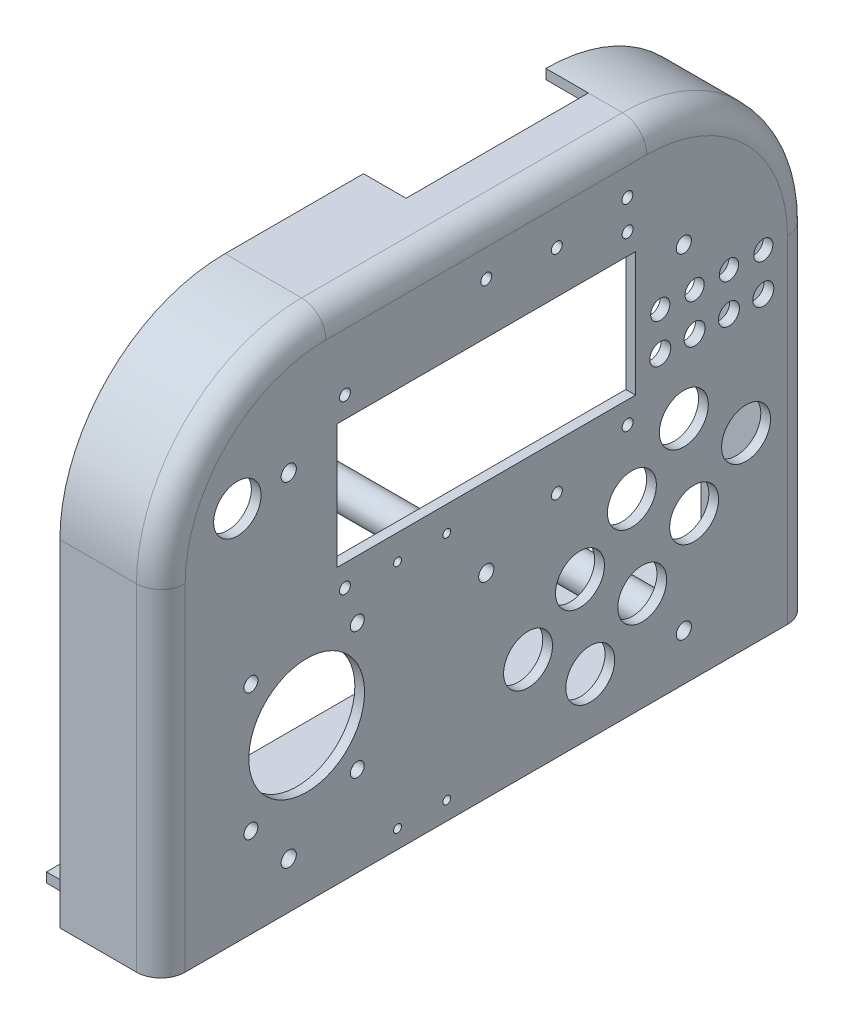
SolidWorks part; units mm, degrees
ref_plane "Front Plane" through (0, 0, 0) normal (0, 0, 1) x (1, 0, 0)
ref_plane "Top Plane" through (0, 0, 0) normal (0, 1, 0) x (1, 0, 0)
ref_plane "Right Plane" through (0, 0, 0) normal (1, 0, 0) x (0, 0, -1)
sketch "Sketch1" plane through (0, 0, 0) normal (1, 0, 0) x (0, 0, -1)
  line L0 (-107.09, -0.1) -> (107.09, -0.1) construction
  line L1 (-49.1, -20.45) -> (49.1, -20.45)
  line L2 (-49.1, -20.45) -> (-49.1, 20.45)
  line L3 (-49.1, 20.45) -> (49.1, 20.45)
  line L4 (49.1, -20.45) -> (49.1, 20.45)
  line L5 (-49.1, -20.45) -> (49.1, 20.45) construction
  line L6 (-49.1, 20.45) -> (49.1, -20.45) construction
  line L11 (-49.1, 29.95) -> (49.1, 29.95) construction
  line L12 (-49.1, 29.95) -> (-49.1, -30.15) construction
  line L13 (-49.1, -30.15) -> (49.1, -30.15) construction
  line L14 (49.1, 29.95) -> (49.1, -30.15) construction
  line L15 (-49.1, 20.45) -> (-82.6403, 20.45) construction
  line L16 (0, 0) -> (0, -0.1) construction
  line L17 (-46.5, -27.6) -> (46.5, -27.6) construction
  line L18 (-46.5, -27.6) -> (-46.5, 27.4) construction
  line L19 (-46.5, 27.4) -> (46.5, 27.4) construction
  line L20 (46.5, -27.6) -> (46.5, 27.4) construction
  line L21 (-46.5, -27.6) -> (46.5, 27.4) construction
  line L22 (-46.5, 27.4) -> (46.5, -27.6) construction
  line L23 (47.911, -49.4394) -> (85.4788, -49.4394) construction
  line L24 (65, -35.1) -> (85.4788, -49.4394) construction
  line L25 (47.911, -49.4394) -> (65, -35.1) construction
  line L26 (0, -0.1) -> (-71.6, -0.1) construction
  line L31 (0, -110.8) -> (0, 54.2) construction
  line L32 (-52.79, 54.2) -> (52.79, 54.2)
  line L33 (-59.95, -60.45) -> (-59.1, -60.45) construction
  line L34 (-42.45, -81.35) -> (-77.45, -81.35) construction
  line L35 (-42.45, -81.35) -> (-42.45, -39.55) construction
  line L36 (-42.45, -39.55) -> (-77.45, -39.55) construction
  line L37 (-77.45, -81.35) -> (-77.45, -39.55) construction
  line L38 (-42.45, -81.35) -> (-77.45, -39.55) construction
  line L39 (-42.45, -39.55) -> (-77.45, -81.35) construction
  line L40 (-107.09, -0.1) -> (-107.09, -110.8)
  line L41 (-107.09, -110.8) -> (107.09, -110.8)
  line L42 (107.09, -0.1) -> (107.09, -110.8)
  line L43 (0, -40.5) -> (0, -46.55) construction
  line L45 (-65, -95.5) -> (65, -95.5) construction
  line L46 (-65, -95.5) -> (-65, 14.5) construction
  line L47 (-65, 14.5) -> (65, 14.5) construction
  line L48 (65, -95.5) -> (65, 14.5) construction
  line L49 (-65, -95.5) -> (65, 14.5) construction
  line L50 (-65, 14.5) -> (65, -95.5) construction
  line L51 (46.42, 54.2) -> (46.42, 37.2) construction
  line L52 (0, 37.2) -> (46.42, 37.2) construction
  line L53 (23.21, 37.2) -> (23.21, -27.6) construction
  line L54 (-42.45, -81.35) -> (0, -81.35) construction
  line L56 (-29.2, -28.8) -> (-13, -28.8) construction
  line L58 (-29.2, -104.8) -> (-13, -104.8) construction
  line L59 (-29.2, -104.8) -> (-29.2, -28.8) construction
  line L60 (-29.2, -28.8) -> (-13, -28.8) construction
  line L61 (-13, -104.8) -> (-13, -28.8) construction
  line L62 (-29.2, -104.8) -> (-13, -28.8) construction
  line L63 (-29.2, -28.8) -> (-13, -104.8) construction
  line L65 (91.15, -3.25) -> (91.15, -9.25) construction
  circle A0 centre (46.5, 27.4) radius 1.8
  circle A1 centre (-46.5, -27.6) radius 1.8
  circle A2 centre (-46.5, 27.4) radius 1.8
  circle A3 centre (46.5, -27.6) radius 1.8
  circle A4 centre (57.25, -0.1) radius 3.15
  circle A5 centre (68.55, -0.1) radius 3.15
  circle A6 centre (79.85, -0.1) radius 3.15
  circle A7 centre (91.15, -0.1) radius 3.15
  circle A9 centre (46.5, 27.4) radius 2.55 construction
  circle A10 centre (46.5, -27.6) radius 2.55 construction
  circle A11 centre (65, -35.1) radius 8.05
  circle A12 centre (85.4788, -49.4394) radius 8.05
  circle A13 centre (68.3898, -63.7788) radius 8.05
  circle A14 centre (51.3007, -78.1182) radius 8.05
  circle A15 centre (34.2117, -92.4576) radius 8.05
  circle A16 centre (47.911, -49.4394) radius 8.05
  circle A17 centre (30.8219, -63.7788) radius 8.05
  circle A18 centre (13.7329, -78.1182) radius 8.05
  circle A25 centre (-77.45, -81.35) radius 2.3
  circle A26 centre (-42.45, -81.35) radius 2.3
  circle A27 centre (-42.45, -39.55) radius 2.3
  circle A28 centre (-77.45, -39.55) radius 2.3
  circle A29 centre (-59.1, -60.45) radius 19.05
  arc A30 (52.79, 54.2) -> (107.09, -0.1) centre (52.79, -0.1) cw
  arc A31 (-52.79, 54.2) -> (-107.09, -0.1) centre (-52.79, -0.1) ccw
  circle A37 centre (-65, -95.5) radius 2.5
  circle A38 centre (65, -95.5) radius 2.5
  circle A39 centre (65, 14.5) radius 2.5
  circle A40 centre (-65, 14.5) radius 2.5
  circle A41 centre (-81.9, 12.7) radius 7.8
  circle A43 centre (0, -46.55) radius 2.5
  circle A44 centre (46.42, 37.2) radius 1.8
  circle A45 centre (0, 37.2) radius 1.8
  circle A46 centre (23.21, 34.55) radius 1.8
  circle A47 centre (23.21, -35.45) radius 1.8
  circle A48 centre (-29.2, -28.8) radius 1.3
  circle A49 centre (-13, -28.8) radius 1.3
  circle A50 centre (-13, -104.8) radius 1.3
  circle A51 centre (-29.2, -104.8) radius 1.3
  circle A52 centre (91.15, -12.7) radius 3.45
  circle A53 centre (79.85, -12.7) radius 3.45
  circle A54 centre (68.55, -12.7) radius 3.45
  circle A55 centre (57.25, -12.7) radius 3.45
  point P1 (0, 0)
  point P11 (46.5, 27.4)
  point P12 (-46.5, -27.6)
  point P16 (-48.3, -27.6)
  point P17 (-46.5, -29.4)
  point P18 (48.3, 27.4)
  point P19 (46.5, 29.2)
  point P22 (-46.5, 29.2)
  point P23 (-48.3, 27.4)
  point P26 (46.5, -29.4)
  point P27 (48.3, -27.6)
  point P30 (54.1, -0.1)
  point P31 (60.4, -0.1)
  point P32 (57.25, 3.05)
  point P36 (65.4, -0.1)
  point P37 (71.7, -0.1)
  point P40 (76.7, -0.1)
  point P41 (83, -0.1)
  point P44 (88, -0.1)
  point P45 (88, -0.1)
  point P47 (-74.1, 12.7)
  point P48 (-64.1, -0.1)
  point P49 (-71.6, 7.4)
  point P52 (0, -0.1)
  point P67 (65, -35.1)
  point P86 (0, -0.1)
  point P92 (0, -28.3)
  point P96 (-59.95, -60.45)
  point P97 (-42.45, -39.55)
  point P98 (-77.45, -39.55)
  point P99 (-77.45, -81.35)
  point P100 (-42.45, -81.35)
  point P107 (0, -40.5)
  point P116 (-71.6, 7.4)
  point P119 (-74.1, 12.7)
  point P120 (-81.9, 20.5)
  point P123 (23.21, 37.2)
  point P124 (0, 37.2)
  point P125 (0, -28.3)
  point P127 (46.42, 37.2)
  point P134 (-21.225, -81.35)
  point P136 (-81.9, 4.9)
  point P141 (-21.1, -28.8)
  point P147 (-21.1, -66.8)
  point P155 (60.7, -12.7)
  point P156 (65.1, -12.7)
  point P157 (72, -12.7)
  point P158 (76.4, -12.7)
  point P159 (83.3, -12.7)
  point P160 (87.7, -12.7)
  point P161 (54.0776, -44.265)
  point P162 (65, -56.4773)
  point P163 (58.8333, -40.2744)
  point P164 (65, -43.15)
  point P167 (57.25, -9.25)
  point P168 (57.25, -3.25)
  dimension "D4" = 3.6
  dimension "D13" = 19.09
  dimension "D14" = 2
  dimension "D16" = 65
  dimension "D19" = 6.3
  dimension "D29" = 18.35
  dimension "D30" = 38.1
  dimension "D31" = 35
  dimension "D32" = 15.6
  dimension "D11" = 16.1
  dimension "D12" = 25
  dimension "D21" = 40
  dimension "D26" = 4.6
  dimension "D34" = 25
  dimension "D36" = 130
  dimension "D37" = 165
  dimension "D39" = 5
  dimension "D42" = 54.3
  dimension "D43" = 15.3
  dimension "D49" = 70
  dimension "D53" = 2.6
  dimension "D48" = 6.9
  dimension "D59" = 13.3273
  dimension "D1" = 98.2
  dimension "D2" = 40.9
  dimension "D5" = 55
  dimension "D6" = 93
  dimension "D7" = 60.1
  dimension "D8" = 98.2
  dimension "D9" = 9.7
  dimension "D10" = 0
  dimension "D15" = 4
  dimension "D17" = 35
  dimension "D18" = 40
  dimension "D20" = 5
  dimension "D22" = 10
  dimension "D23" = 5
  dimension "D24" = 5
  dimension "D25" = 5
  dimension "D27" = 35
  dimension "D28" = 41.8
  dimension "D33" = 25
  dimension "D35" = 33.5403
  dimension "D38" = 110
  dimension "D40" = 214.18
  dimension "D41" = 5
  dimension "D44" = 6.05
  dimension "D45" = 12.2
  dimension "D46" = 46.42
  dimension "D47" = 17
  dimension "D50" = 15
  dimension "D51" = 76
  dimension "D52" = 16.2
  dimension "D54" = 6
  dimension "D55" = 13
  dimension "D56" = 6.65
  dimension "D57" = 6.2082
  dimension "D58" = 6
extrude "Boss-Extrude1" add sketch "Sketch1" along normal blind 3.2
sketch "Sketch3" plane through (0, 0, 0) normal (-1, 0, 0) x (0, 0, 1)
  line L0 (-103.89, -0.1) -> (-103.89, -107.6)
  line L1 (-103.89, -107.6) -> (103.89, -107.6)
  line L2 (103.89, -107.6) -> (103.89, -0.1)
  line L3 (52.79, 51) -> (-52.79, 51)
  line L4 (-107.09, -0.1) -> (-107.09, -110.8)
  line L5 (-107.09, -110.8) -> (107.09, -110.8)
  line L6 (107.09, -110.8) -> (107.09, -0.1)
  line L7 (52.79, 54.2) -> (-52.79, 54.2)
  line L8 (-107.09, -0.1) -> (-107.09, -110.8)
  line L9 (-107.09, -110.8) -> (107.09, -110.8)
  line L10 (107.09, -110.8) -> (107.09, -0.1)
  line L11 (52.79, 54.2) -> (-52.79, 54.2)
  arc A0 (103.89, -0.1) -> (52.79, 51) centre (52.79, -0.1) ccw
  arc A1 (-52.79, 51) -> (-103.89, -0.1) centre (-52.79, -0.1) ccw
  arc A2 (-52.79, 54.2) -> (-107.09, -0.1) centre (-52.79, -0.1) ccw
  arc A3 (107.09, -0.1) -> (52.79, 54.2) centre (52.79, -0.1) ccw
  arc A4 (-52.79, 54.2) -> (-107.09, -0.1) centre (-52.79, -0.1) ccw
  arc A5 (107.09, -0.1) -> (52.79, 54.2) centre (52.79, -0.1) ccw
  dimension "D3" = 207.78
  dimension "D4" = 158.6
  dimension "D1" = 0
  dimension "D2" = 3.2
extrude "Boss-Extrude2" add sketch "Sketch3" along normal blind 30
fillet "Fillet1" radius 4.8 5 edges at (0, -53.85, -103.89) (0, 36.0332, -88.9232) (0, 51, 0) (0, 36.0332, 88.9232) (0, -53.85, 103.89)
fillet "Fillet2" radius 8 5 edges at (3.2, -55.45, -107.09) (3.2, 38.2959, -91.1859) (3.2, 54.2, 0) (3.2, 38.2959, 91.1859) (3.2, -55.45, 107.09)
sketch "Sketch6" plane through (0, 0, 0) normal (-1, 0, 0) x (0, 0, 1)
  line L0 (-65, -95.5) -> (65, 14.5) construction
  line L1 (65, -95.5) -> (-65, 14.5) construction
  line L2 (0, -40.5) -> (0, -46.55) construction
  circle A4 centre (65, 14.5) radius 5.25
  circle A5 centre (65, 14.5) radius 2.5
  circle A8 centre (-65, 14.5) radius 5.25
  circle A9 centre (-65, 14.5) radius 2.5
  circle A12 centre (-65, -95.5) radius 5.25
  circle A13 centre (-65, -95.5) radius 2.5
  circle A14 centre (65, -95.5) radius 5.25
  circle A15 centre (65, -95.5) radius 2.5
  circle A18 centre (0, -46.55) radius 2.5
  circle A19 centre (0, -46.55) radius 5.25
  point P2 (0, -40.5)
  point P4 (-65, 14.5)
  point P13 (0, -46.55)
  point P15 (65, 14.5)
  dimension "D10" = 10.5
  dimension "D9" = 5
extrude "Boss-Extrude3" add sketch "Sketch6" along normal blind 50
sketch "Sketch12" plane through (-30, 0, 0) normal (-1, 0, 0) x (0, 0, 1)
  line L0 (96.49, -107.6) -> (96.49, -110.8)
  line L1 (-96.49, -107.6) -> (-96.49, -110.8)
  line L2 (107.09, -110.8) -> (96.49, -110.8) construction
  line L3 (-96.49, -107.6) -> (96.49, -107.6)
  line L4 (-96.49, -110.8) -> (-107.09, -110.8) construction
  line L13 (52.79, 54.2) -> (-52.79, 54.2)
  line L14 (-107.09, -0.1) -> (-107.09, -110.8)
  line L15 (-107.09, -110.8) -> (107.09, -110.8)
  line L16 (107.09, -110.8) -> (107.09, -0.1)
  line L26 (-107.09, -0.1) -> (-107.09, -110.8) construction
  line L27 (-96.49, -110.8) -> (96.49, -110.8)
  line L28 (107.09, -110.8) -> (107.09, -0.1) construction
  arc A4 (-52.79, 54.2) -> (-107.09, -0.1) centre (-52.79, -0.1) ccw
  arc A5 (107.09, -0.1) -> (52.79, 54.2) centre (52.79, -0.1) ccw
  point P15 (-96.49, -107.6)
  point P16 (96.49, -107.6)
  dimension "D2" = 10.6
  dimension "D3" = 10.6
  dimension "D4" = 3.2
  dimension "D1" = 0
extrude "Boss-Extrude7" add sketch "Sketch12" along normal blind 15
sketch "Sketch8" plane through (0, -110.8, 0) normal (0, -1, 0) x (1, 0, 0)
  line L0 (3.2, 99.09) -> (-30, 99.09) construction
  line L1 (-30, -107.09) -> (-30, -96.49) construction
  line L2 (-4.8, 107.09) -> (-4.8, 47.09) construction
  line L3 (-6, 77.09) -> (-24.6, 77.09) construction
  line L5 (-34.6, 77.09) -> (-14.6, 77.09) construction
  line L6 (3.2, -99.09) -> (-30, -99.09) construction
  line L7 (-4.8, -107.09) -> (-4.8, -47.09) construction
  line L8 (-6, -77.09) -> (-24.6, -77.09) construction
  line L10 (-14.6, -77.09) -> (-34.6, -77.09) construction
  circle A0 centre (-14.6, 77.09) radius 2.3
  circle A1 centre (-34.6, 77.09) radius 2.3
  circle A2 centre (-14.6, -77.09) radius 2.3
  circle A3 centre (-34.6, -77.09) radius 2.3
  point P8 (-4.8, 77.1)
  point P9 (-13.4, 99.09)
  point P16 (-24.6, 77.09)
  point P24 (-4.8, -77.09)
  point P25 (-13.4, -99.09)
  point P32 (-24.6, -77.09)
  dimension "D3" = 4.6
  dimension "D6" = 4.6
  dimension "D1" = 60
  dimension "D2" = 20
  dimension "D4" = 60
  dimension "D5" = 20
  dimension "D7" = 22
  dimension "D8" = 22
  dimension "D9" = 19.8
  dimension "D10" = 19.8
extrude "Cut-Extrude2" cut sketch "Sketch8" against normal blind 10
sketch "Sketch19" plane through (0, 54.2, 0) normal (0, 1, 0) x (1, 0, 0)
  line L0 (-30, 52.79) -> (-16, 52.79)
  line L1 (-4.8, 52.79) -> (-30, 52.79) construction
  line L2 (-16, 52.79) -> (-16, -7.21)
  line L3 (-16, -7.21) -> (-30, -7.21)
  line L4 (-30, -52.79) -> (-30, 52.79) construction
  line L5 (-30, -7.21) -> (-30, 52.79)
  dimension "D1" = 14
  dimension "D2" = 60
extrude "Cut-Extrude7" cut sketch "Sketch19" against normal blind 10
